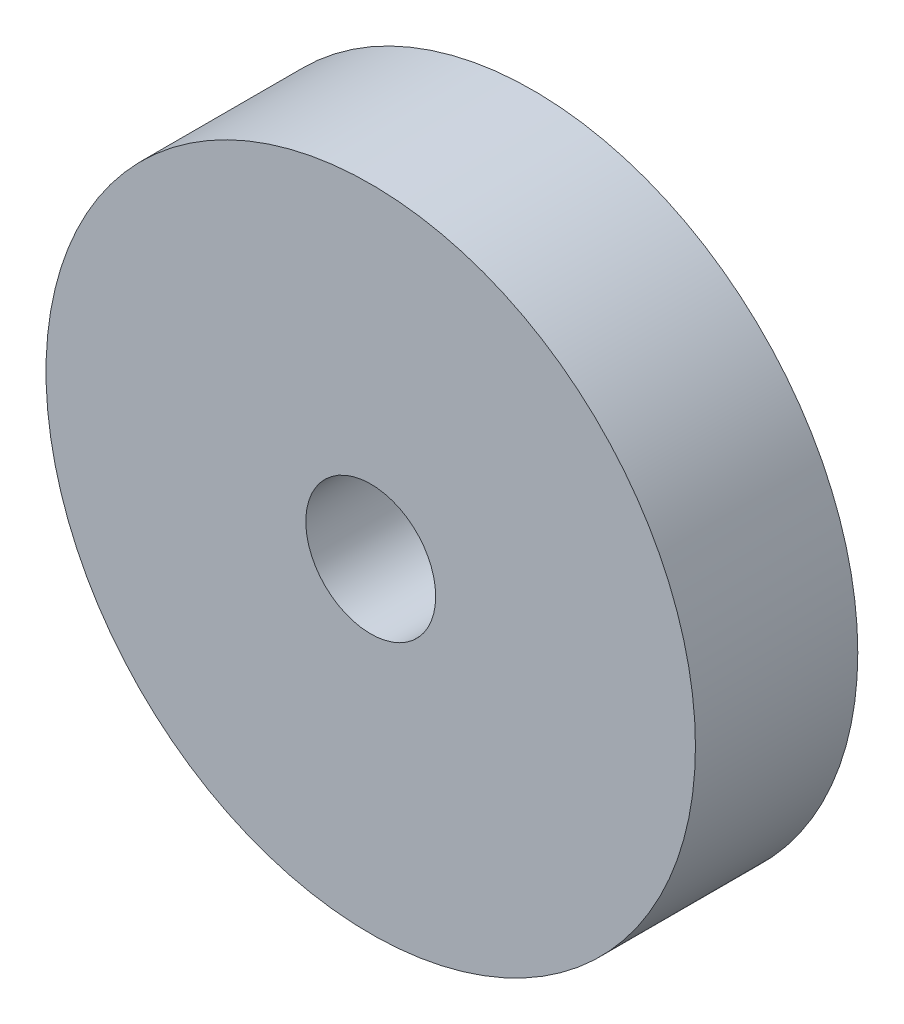
SolidWorks part; units mm, degrees
ref_plane "Plan de face" through (0, 0, 0) normal (0, 0, 1) x (1, 0, 0)
ref_plane "Plan de dessus" through (0, 0, 0) normal (0, 1, 0) x (1, 0, 0)
ref_plane "Plan de droite" through (0, 0, 0) normal (1, 0, 0) x (0, 0, -1)
sketch "Esquisse1" plane through (0, 0, 0) normal (0, 0, 1) x (1, 0, 0)
  circle A0 centre (0, 280) radius 20
extrude "Boss.-Extru.1" add sketch "Esquisse1" along normal blind 10
sketch "Esquisse2" plane through (0, 0, 10) normal (0, 0, 1) x (1, 0, 0)
  circle A0 centre (0, 280) radius 4 construction
  circle A1 centre (0, 280) radius 4
extrude "Enlèv. mat.-Extru.1" cut sketch "Esquisse2" against normal through all
